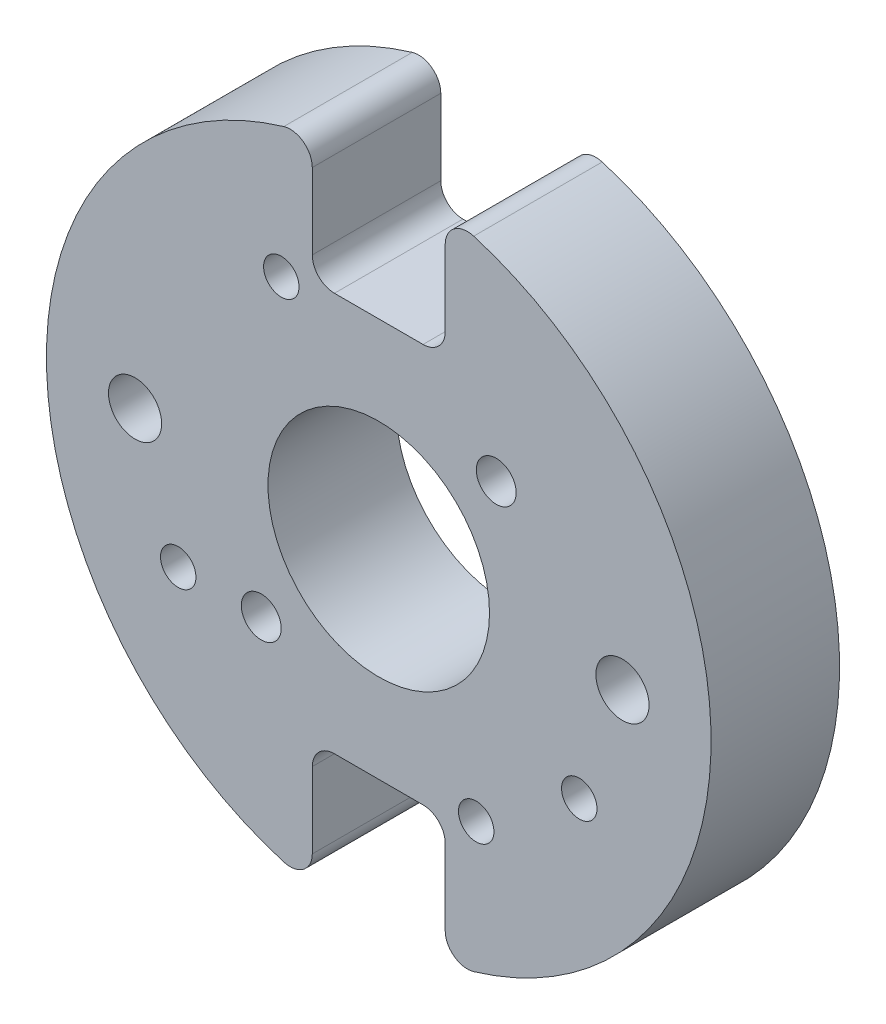
SolidWorks part; units mm, degrees
ref_plane "Front Plane" through (0, 0, 0) normal (0, 0, 1) x (1, 0, 0)
ref_plane "Top Plane" through (0, 0, 0) normal (0, 1, 0) x (1, 0, 0)
ref_plane "Right Plane" through (0, 0, 0) normal (1, 0, 0) x (0, 0, -1)
sketch "Sketch1" plane through (0, 0, 0) normal (0, 0, 1) x (1, 0, 0)
  circle A0 centre (0, 0) radius 15
  circle A1 centre (0, 0) radius 5
  dimension "D1" = 10
  dimension "D2" = 30
extrude "Boss-Extrude1" add sketch "Sketch1" along normal blind 5.8
hole_wizard "M2 Clearance Hole1" positions "Sketch4" profile "Sketch3" hole size "M2" standard "Ansi Metric"
sketch "Sketch4" plane through (0, 0, 5.8) normal (0, 0, 1) x (1, 0, 0)
  line L0 (0, 0) -> (11, 0) construction
  line L2 (0, 0) -> (-11, 0) construction
  point P0 (-11, 0)
  point P3 (11, 0)
  dimension "D1" = 22
sketch "Sketch3" plane through (-11, 0, 5.8) normal (1, 0, 0) x (0, -1, 0)
  line L0 (0, 0) -> (0, 26.121)
  line L1 (0, 26.121) -> (1.2, 25.4)
  line L2 (1.2, 25.4) -> (1.2, 0)
  line L5 (1.2, 0) -> (0, 0)
  line L10 (0, 26.121) -> (-1.2, 25.4) construction
  line L11 (0, -6.35) -> (0, 107.95) construction
  dimension "Hole Dia." = 2.4
  dimension "Hole Depth" = 25.4
  dimension "Drill Angle" = 118
hole_wizard "M1.6 Clearance Hole1" positions "Sketch6" profile "Sketch5" hole size "M1.6" standard "Ansi Metric"
sketch "Sketch6" plane through (0, 0, 5.8) normal (0, 0, 1) x (1, 0, 0)
  line L0 (0, 0) -> (11, 0) construction
  line L2 (0, 0) -> (5.3033, 5.3033) construction
  line L4 (0, 0) -> (-5.3033, -5.3033) construction
  point P0 (5.3033, 5.3033)
  point P1 (-5.3033, -5.3033)
  dimension "D1" = 45
  dimension "D2" = 15
sketch "Sketch5" plane through (5.3033, 5.3033, 5.8) normal (1, 0, 0) x (0, -1, 0)
  line L0 (0, 0) -> (0, 25.9408)
  line L1 (0, 25.9408) -> (0.9, 25.4)
  line L2 (0.9, 25.4) -> (0.9, 0)
  line L5 (0.9, 0) -> (0, 0)
  line L10 (0, 25.9408) -> (-0.9, 25.4) construction
  line L11 (0, -6.35) -> (0, 107.95) construction
  dimension "Hole Dia." = 1.8
  dimension "Hole Depth" = 25.4
  dimension "Drill Angle" = 118
sketch "Sketch8" plane through (0, 0, 5.8) normal (0, 0, 1) x (1, 0, 0)
  line L0 (0, 0) -> (0, -15) construction
  line L1 (3, -15) -> (-3, -15)
  line L2 (-3, -15) -> (-3, -9)
  line L3 (-3, -9) -> (3, -9)
  line L4 (3, -15) -> (3, -9)
  line L5 (0, 0) -> (-15, 0) construction
  line L6 (3, 15) -> (3, 9)
  line L7 (-3, 9) -> (3, 9)
  line L8 (-3, 15) -> (-3, 9)
  line L9 (3, 15) -> (-3, 15)
  circle A0 centre (0, 0) radius 15 construction
  point P10 (0, -9)
  point P11 (0, 9)
  dimension "D1" = 6
  dimension "D2" = 3
extrude "Cut-Extrude1" cut sketch "Sketch8" against normal through all
fillet "Fillet1" radius 1 8 edges at (3, 14.6969, 2.9) (3, 9, 2.9) (-3, 9, 2.9) (-3, 14.6969, 2.9) (3, -14.6969, 2.9) (-3, -14.6969, 2.9) (-3, -9, 2.9) (3, -9, 2.9)
hole_wizard "M2x0.4 Tapped Hole1" positions "Sketch10" profile "Sketch9" tap size "M2x0.4" standard "Ansi Metric"
sketch "Sketch10" plane through (0, 0, 5.8) normal (0, 0, 1) x (1, 0, 0)
  line L0 (-4.3982, 8.4488) -> (0, 0) construction
  line L1 (0, 0) -> (4.3982, -8.4488) construction
  line L3 (0, 0) -> (0, 11.0917) construction
  point P0 (-4.3982, 8.4488)
  point P1 (4.3982, -8.4488)
  dimension "D1" = 19.05
  dimension "D2" = 27.5
sketch "Sketch9" plane through (-4.3982, 8.4488, 5.8) normal (1, 0, 0) x (0, -1, 0)
  line L0 (0, 0) -> (0, 6.4802)
  line L1 (0, 6.4802) -> (0.8, 5.9995)
  line L2 (0.8, 5.9995) -> (0.8, 0)
  line L5 (0.8, 0) -> (0, 0)
  line L10 (0, 6.4802) -> (-0.8, 5.9995) construction
  line L11 (0, -6.35) -> (0, 107.95) construction
  dimension "Tap Drill Dia." = 1.6
  dimension "Tap Drill Depth" = 5.9995
  dimension "Drill Angle" = 118
hole_wizard "M2x0.4 Tapped Hole2" positions "Sketch12" profile "Sketch11" tap size "M2x0.4" standard "Ansi Metric"
sketch "Sketch12" plane through (0, 0, 0) normal (0, 0, -1) x (-1, 0, 0)
  line L0 (0, 0) -> (9.0518, -5.226) construction
  line L2 (0, 0) -> (0, 10.4521) construction
  line L4 (0, 0) -> (-9.0518, -5.2261) construction
  point P0 (9.0518, -5.226)
  point P18 (-9.0518, -5.2261)
  point P19 (0, 10.4521)
  dimension "D2" = 10.4521
  dimension "D1" = 3
sketch "Sketch11" plane through (-9.0518, -5.226, 0) normal (1, 0, 0) x (0, 1, 0)
  line L0 (0, 0) -> (0, 6.4802)
  line L1 (0, 6.4802) -> (0.8, 5.9995)
  line L2 (0.8, 5.9995) -> (0.8, 0)
  line L5 (0.8, 0) -> (0, 0)
  line L10 (0, 6.4802) -> (-0.8, 5.9995) construction
  line L11 (0, -6.35) -> (0, 107.95) construction
  dimension "Tap Drill Dia." = 1.6
  dimension "Tap Drill Depth" = 5.9995
  dimension "Drill Angle" = 118
